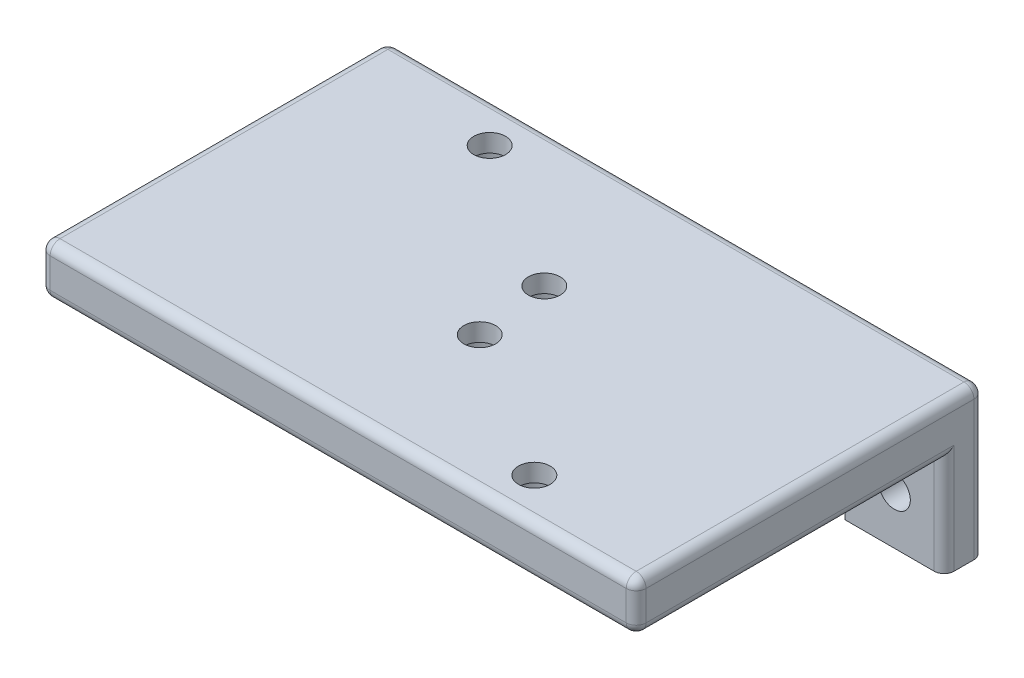
SolidWorks part; units mm, degrees
ref_plane "前视基准面" through (0, 0, 0) normal (0, 0, 1) x (1, 0, 0)
ref_plane "上视基准面" through (0, 0, 0) normal (0, 1, 0) x (1, 0, 0)
ref_plane "右视基准面" through (0, 0, 0) normal (1, 0, 0) x (0, 0, -1)
sketch "草图1" plane through (0, 0, 0) normal (0, 0, 1) x (1, 0, 0)
  line L0 (20, 0) -> (30, 0)
  line L1 (-30, 15) -> (30, 15)
  line L2 (-30, 15) -> (-30, 0)
  line L3 (-30, 0) -> (-20, 0)
  line L4 (30, 15) -> (30, 0)
  line L6 (20, 0) -> (20, 10)
  line L7 (20, 10) -> (-20, 10)
  line L8 (-20, 0) -> (-20, 10)
  circle A0 centre (-25, 5) radius 1.6
  circle A1 centre (25, 5) radius 1.6
  point P8 (0, 15)
  point P10 (0, 10)
  dimension "D8" = 3.2
  dimension "D1" = 60
  dimension "D2" = 15
  dimension "D3" = 40
  dimension "D4" = 10
  dimension "D5" = 5
  dimension "D6" = 5
  dimension "D7" = 5
extrude "凸台-拉伸1" add sketch "草图1" along normal blind 4
sketch "草图2" plane through (0, 0, 4) normal (0, 0, 1) x (1, 0, 0)
  line L0 (30, 0) -> (30, 15) construction
  line L1 (-30, 15) -> (30, 15)
  line L2 (-30, 15) -> (-30, 10)
  line L3 (-30, 10) -> (30, 10)
  line L4 (30, 15) -> (30, 10)
  line L5 (-20, 10) -> (20, 10) construction
extrude "凸台-拉伸2" add sketch "草图2" along normal blind 31
sketch "草图8" plane through (0, 10, 0) normal (0, -1, 0) x (1, 0, 0)
  line L0 (-15.5, 4.25) -> (-0.5, 13.75) construction
  line L1 (0.5, 21.25) -> (15.5, 30.75) construction
  line L2 (-20, 0) -> (20, 0) construction
  circle A0 centre (-15.5, 4.25) radius 1.6
  circle A1 centre (-0.5, 13.75) radius 1.6
  circle A2 centre (0.5, 21.25) radius 1.6
  circle A3 centre (15.5, 30.75) radius 1.6
  point P5 (-8, 9)
  point P13 (8, 26)
  dimension "D3" = 3.2
  dimension "D6" = 3.2
  dimension "D1" = 15
  dimension "D2" = 9.5
  dimension "D4" = 15
  dimension "D5" = 9.5
  dimension "D7" = 8
  dimension "D8" = 9
  dimension "D9" = 26
  dimension "D10" = 8
extrude "切除-拉伸1" cut sketch "草图8" against normal through all
sketch "草图9" plane through (0, 10, 0) normal (0, -1, 0) x (1, 0, 0)
  circle A0 centre (-15.5, 4.25) radius 3
  circle A1 centre (-0.5, 13.75) radius 3
  circle A2 centre (0.5, 21.25) radius 3
  circle A3 centre (15.5, 30.75) radius 3
  dimension "D1" = 6
extrude "切除-拉伸2" cut sketch "草图9" against normal blind 3.2
fillet "圆角2" radius 1 18 edges at (-20, 5, 0) (20, 5, 0) (30, 15, 17.5) (0, 15, 35) (-30, 15, 17.5) (0, 15, 0) (30, 12.5, 35) (-30, 12.5, 35) (30, 7.5, 0) (-30, 7.5, 0) (30, 10, 19.5) (-30, 10, 19.5) (0, 10, 35) (30, 5, 4) (-30, 5, 4) (0, 10, 0) (-20, 10, 2) (20, 10, 2)
